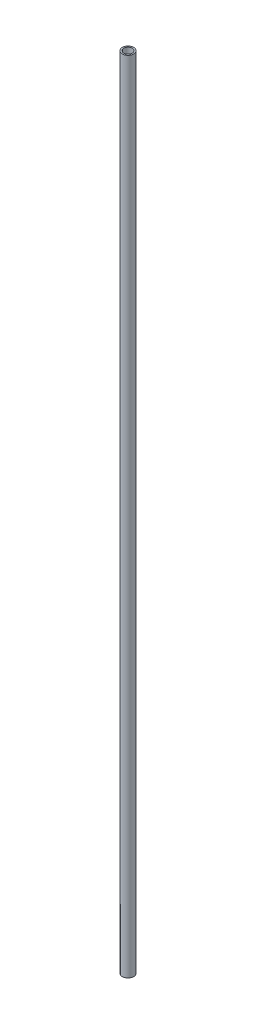
SolidWorks part; units mm, degrees
material "Parylene"
ref_plane "Front Plane" through (0, 0, 0) normal (0, 0, 1) x (1, 0, 0)
ref_plane "Top Plane" through (0, 0, 0) normal (0, 1, 0) x (1, 0, 0)
ref_plane "Right Plane" through (0, 0, 0) normal (1, 0, 0) x (0, 0, -1)
sketch "Sketch1" plane through (0, 0, 0) normal (0, 1, 0) x (1, 0, 0)
  circle A0 centre (0, 0) radius 0.75
  circle A1 centre (0, 0) radius 1
extrude "Boss-Extrude1" add sketch "Sketch1" along normal blind 140
